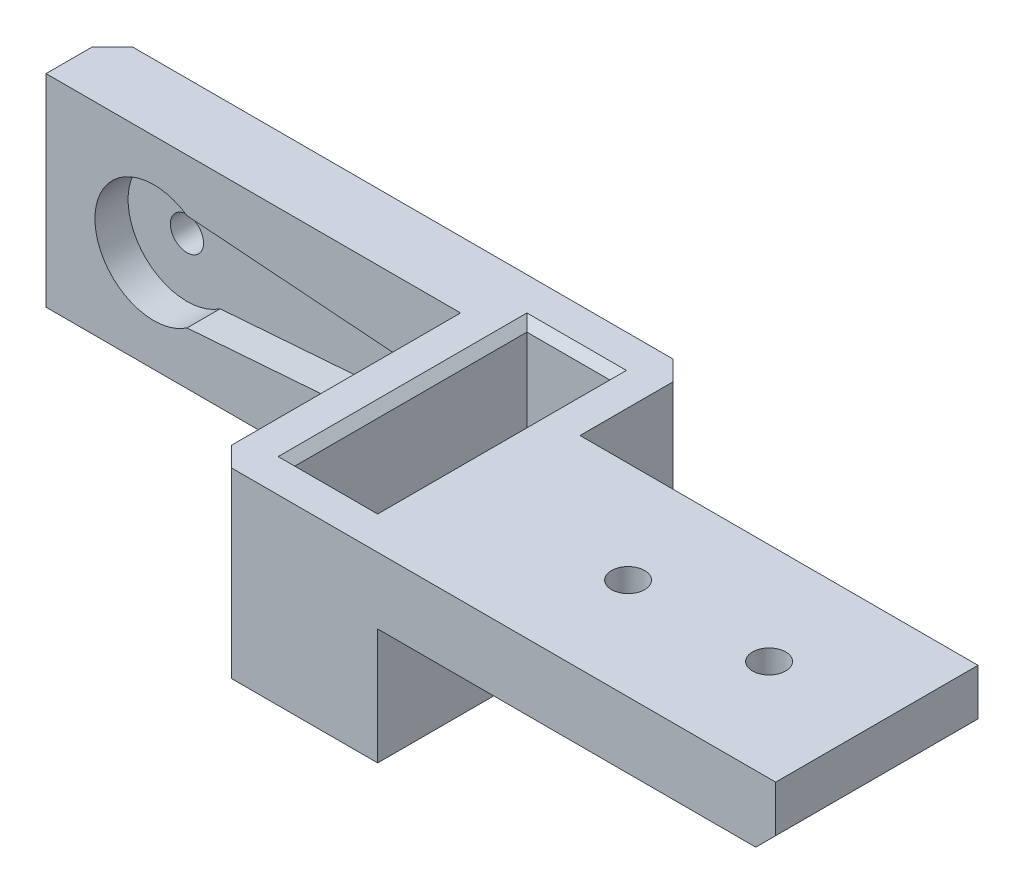
SolidWorks part; units mm, degrees
ref_plane "Front Plane" through (0, 0, 0) normal (0, 0, 1) x (1, 0, 0)
ref_plane "Top Plane" through (0, 0, 0) normal (0, 1, 0) x (1, 0, 0)
ref_plane "Right Plane" through (0, 0, 0) normal (1, 0, 0) x (0, 0, -1)
sketch "Sketch1" plane through (0, 0, 0) normal (0, 0, 1) x (1, 0, 0)
  line L1 (-35.5488, 11.7605) -> (-0.5488, 11.7605)
  line L2 (-35.5488, 11.7605) -> (-35.5488, -0.4395)
  line L3 (-35.5488, -0.4395) -> (-0.5488, -0.4395)
  line L4 (-0.5488, 11.7605) -> (-0.5488, -0.4395)
  dimension "D1" = 35
  dimension "D2" = 12.2
extrude "Boss-Extrude1" add sketch "Sketch1" along normal blind 4
sketch "Sketch2" plane through (0, 0, 4) normal (0, 0, 1) x (1, 0, 0)
  line L0 (-0.5488, 11.7605) -> (-35.5488, 11.7605) construction
  line L3 (-35.5488, 11.7605) -> (-35.5488, -0.4395) construction
  circle A0 centre (-29.0488, 5.6605) radius 1
  dimension "D1" = 2
  dimension "D2" = 6.1
  dimension "D3" = 6.5
extrude "Cut-Extrude1" cut sketch "Sketch2" against normal through all contours A0
sketch "Sketch3" plane through (0, 0, 4) normal (0, 0, 1) x (1, 0, 0)
  line L0 (-35.5488, -0.4395) -> (-0.5488, -0.4395) construction
  line L1 (-0.5488, 11.7605) -> (-10.5488, 11.7605)
  line L2 (-0.5488, 11.7605) -> (-0.5488, -0.4395)
  line L3 (-0.5488, -0.4395) -> (-10.5488, -0.4395)
  line L4 (-10.5488, 11.7605) -> (-10.5488, -0.4395)
  dimension "D1" = 10
extrude "Boss-Extrude2" add sketch "Sketch3" along normal blind 15
sketch "Sketch4" plane through (-0.5488, 0, 0) normal (1, 0, 0) x (0, 0, -1)
  line L1 (-19, 11.7605) -> (-6.8, 11.7605)
  line L2 (-19, 11.7605) -> (-19, 7.7605)
  line L3 (-19, 7.7605) -> (-6.8, 7.7605)
  line L4 (-6.8, 11.7605) -> (-6.8, 7.7605)
  dimension "D1" = 12.2
  dimension "D2" = 4
  dimension "D3" = 12.2
extrude "Boss-Extrude3" add sketch "Sketch4" along normal blind 24 contours L2 L1 L4 L3
sketch "Sketch5" plane through (0, 7.7605, 0) normal (0, -1, 0) x (1, 0, 0)
  line L0 (23.4512, 19) -> (23.4512, 6.8) construction
  line L1 (23.4512, 19) -> (-0.5488, 19) construction
  line L2 (16.9512, 12.9) -> (8.4512, 12.9) construction
  circle A0 centre (16.9512, 12.9) radius 1
  circle A1 centre (8.4512, 12.9) radius 1
  dimension "D3" = 2
  dimension "D5" = 2
  dimension "D1" = 6.5
  dimension "D2" = 6.1
  dimension "D4" = 8.5
extrude "Cut-Extrude2" cut sketch "Sketch5" against normal through all and the other way through all contours A0 | A1
sketch "Sketch7" plane through (0, 0, 0) normal (0, 0, -1) x (-1, 0, 0)
  line L0 (0.5488, 11.7605) -> (35.5488, 11.7605) construction
  line L1 (23.0488, 5.6605) -> (19.2988, 7.8256)
  line L2 (19.2988, 7.8256) -> (19.2988, 3.4954)
  line L3 (19.2988, 3.4954) -> (23.0488, 5.6605)
  line L5 (35.5488, 11.7605) -> (35.5488, -0.4395) construction
  circle A0 centre (20.5488, 5.6605) radius 1.25 construction
  dimension "D2" = 2.5
  dimension "D1" = 6.1
  dimension "D3" = 15
  dimension "D4" = 3.75
extrude "Cut-Extrude3" cut sketch "Sketch7" against normal blind 0.5
chamfer "Chamfer1" distance 1.2 angle 45 10 edges at (23.4512, 7.7605, 12.9) (-35.5488, 5.6605, 0) (-0.5488, 3.6605, 19) (-0.5488, 5.6605, 0) (-10.5488, -0.4395, 11.5) (-10.5488, 11.7605, 11.5) (-5.5488, -0.4395, 19) (-10.5488, 5.6605, 19) (-18.0488, -0.4395, 0) (-0.5488, -0.4395, 9.5)
sketch "Sketch24" plane through (0, 0, 4) normal (0, 0, 1) x (1, 0, 0)
  line L0 (-29.0488, 5.6605) -> (-14.6488, 5.6605) construction
  line L1 (-29.0488, 5.6605) -> (-26.6857, 5.6605) construction
  line L6 (-29.0488, 5.6605) -> (-27.0488, 5.6605) construction
  line L8 (-27.0488, 2.7275) -> (-14.6488, 3.6605)
  line L10 (-14.6488, 7.6605) -> (-27.0488, 8.5935)
  arc A0 (-27.0488, 8.5935) -> (-27.0488, 2.7275) centre (-29.0488, 5.6605) ccw
  arc A1 (-14.6488, 3.6605) -> (-14.6488, 7.6605) centre (-14.6488, 5.6605) ccw
  dimension "D1" = 7.1
  dimension "D2" = 4
  dimension "D3" = 14.4
  dimension "D4" = 12.4
  dimension "D5" = 12.4
extrude "Cut-Extrude17" cut sketch "Sketch24" against normal blind 2
sketch "Sketch25" plane through (0, 7.7605, 0) normal (0, -1, 0) x (1, 0, 0)
  line L0 (16.9512, 12.9) -> (2.5512, 12.9) construction
  line L1 (16.9512, 12.9) -> (14.5882, 12.9) construction
  line L6 (16.9512, 12.9) -> (14.9512, 12.9) construction
  line L7 (2.5512, 14.9) -> (14.9512, 15.833)
  line L9 (14.9512, 9.967) -> (2.5512, 10.9)
  arc A0 (14.9512, 9.967) -> (14.9512, 15.833) centre (16.9512, 12.9) ccw
  arc A1 (2.5512, 14.9) -> (2.5512, 10.9) centre (2.5512, 12.9) ccw
  dimension "D1" = 7.1
  dimension "D2" = 4
  dimension "D3" = 14.4
  dimension "D4" = 12.4
  dimension "D5" = 12.4
extrude "Cut-Extrude18" cut sketch "Sketch25" against normal blind 2
sketch "Sketch26" plane through (0, 11.7605, 0) normal (0, 1, 0) x (1, 0, 0)
  line L0 (-1.7488, 0) -> (-34.3488, 0) construction
  line L1 (-8.0488, -2.5) -> (-3.0488, -2.5)
  line L2 (-8.0488, -2.5) -> (-8.0488, -16.5)
  line L3 (-8.0488, -16.5) -> (-3.0488, -16.5)
  line L4 (-3.0488, -2.5) -> (-3.0488, -16.5)
  line L5 (-10.5488, -17.8) -> (-10.5488, -4) construction
  line L6 (-0.5488, -6.8) -> (-0.5488, -1.2) construction
  line L7 (23.4512, -19) -> (-9.3488, -19) construction
  dimension "D1" = 2.5
  dimension "D2" = 2.5
  dimension "D3" = 2.5
  dimension "D4" = 2.5
extrude "Cut-Extrude19" cut sketch "Sketch26" against normal through all
chamfer "Chamfer2" distance 0.5 angle 45 8 edges at (-3.0488, -0.4395, 9.5) (-5.5488, -0.4395, 2.5) (-8.0488, -0.4395, 9.5) (-5.5488, -0.4395, 16.5) (-3.0488, 11.7605, 9.5) (-5.5488, 11.7605, 2.5) (-5.5488, 11.7605, 16.5) (-8.0488, 11.7605, 9.5)
